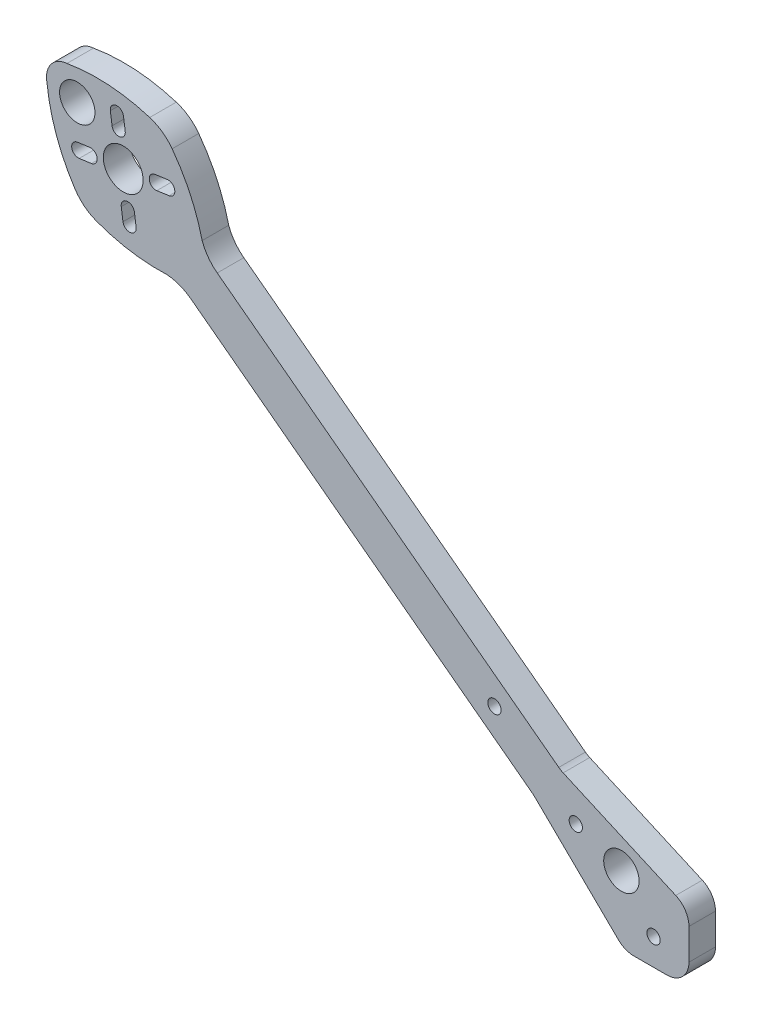
SolidWorks part; units mm, degrees
material "Thornel Mat VMA"
ref_plane "Alzado" through (0, 0, 0) normal (0, 0, 1) x (1, 0, 0)
ref_plane "Planta" through (0, 0, 0) normal (0, 1, 0) x (1, 0, 0)
ref_plane "Vista lateral" through (0, 0, 0) normal (1, 0, 0) x (0, 0, -1)
sketch "Croquis1" plane through (0, 0, 0) normal (0, 0, 1) x (1, 0, 0)
  line L0 (-166.1256, 84.824) -> (-181.6394, 96.5144) construction
  line L1 (-181.6394, 96.5144) -> (-187.6575, 88.5281) construction
  line L2 (-187.6575, 88.5281) -> (-171.8329, 76.6034) construction
  line L3 (-136.7303, 61.4124) -> (-136.7303, 68.4084)
  line L4 (-139.7056, 72.9801) -> (-165.1413, 84.2454)
  line L5 (-136.7303, 56.4124) -> (-264.512, 152.7028) construction
  line L6 (-141.7303, 56.4124) -> (-149.1592, 56.4124)
  line L7 (-152.6561, 57.8386) -> (-171.6025, 76.3779)
  line L8 (-264.512, 152.7028) -> (-274.8943, 160.5264) construction
  line L9 (-264.512, 152.7028) -> (-266.1473, 164.3384) construction
  line L11 (-267.4239, 162.6443) -> (-267.0343, 159.8715)
  line L15 (-264.0635, 160.289) -> (-264.4531, 163.0618)
  line L19 (-267.6327, 164.1297) -> (-267.4239, 162.6443) construction
  line L20 (-267.4239, 162.6443) -> (-264.4531, 163.0618) construction
  line L21 (-266.8255, 158.3861) -> (-267.0343, 159.8715) construction
  line L22 (-267.0343, 159.8715) -> (-264.0635, 160.289) construction
  line L23 (-254.5705, 155.6147) -> (-257.3433, 155.225)
  line L24 (-256.9258, 152.2542) -> (-254.153, 152.6439)
  line L25 (-261.6001, 142.7613) -> (-261.9898, 145.534)
  line L26 (-264.9606, 145.1165) -> (-264.5709, 142.3438)
  line L27 (-274.4535, 149.7908) -> (-271.6808, 150.1805)
  line L28 (-272.0983, 153.1513) -> (-274.871, 152.7616)
  line L29 (-172.0904, 76.7974) -> (-249.3006, 134.9795)
  line L30 (-264.512, 152.7028) -> (-273.5392, 140.7232) construction
  line L31 (-263.0855, 142.5525) -> (-262.8767, 141.0671) construction
  line L32 (-274.8943, 160.5264) -> (-282.8806, 166.5445) construction
  line L33 (-262.8767, 141.0671) -> (-262.3693, 137.4568) construction
  line L34 (-274.6623, 151.2762) -> (-276.1477, 151.0675) construction
  line L35 (-276.1477, 151.0675) -> (-279.6136, 150.5804) construction
  line L36 (-165.8148, 84.5898) -> (-243.2825, 142.9659)
  circle A0 centre (-180.6553, 89.5122) radius 1.5
  circle A1 centre (-162.2906, 75.6734) radius 1.5
  circle A2 centre (-151.9803, 71.6624) radius 4
  circle A3 centre (-144.7167, 62.4305) radius 1.5
  circle A5 centre (-136.7303, 56.4124) radius 10 construction
  circle A6 centre (-136.7303, 56.4124) radius 160 construction
  circle A7 centre (-264.512, 152.7028) radius 4.5
  circle A8 centre (-274.8943, 160.5264) radius 4
  arc A9 (-267.4239, 162.6443) -> (-264.4531, 163.0618) centre (-265.9385, 162.853) cw
  arc A10 (-267.0343, 159.8715) -> (-264.0635, 160.289) centre (-265.5489, 160.0803) ccw
  arc A11 (-254.5705, 155.6147) -> (-254.153, 152.6439) centre (-254.3618, 154.1293) cw
  arc A12 (-257.3433, 155.225) -> (-256.9258, 152.2542) centre (-257.1345, 153.7396) ccw
  arc A13 (-261.6001, 142.7613) -> (-264.5709, 142.3438) centre (-263.0855, 142.5525) cw
  arc A14 (-261.9898, 145.534) -> (-264.9606, 145.1165) centre (-263.4752, 145.3253) ccw
  arc A15 (-274.4535, 149.7908) -> (-274.871, 152.7616) centre (-274.6623, 151.2762) cw
  arc A16 (-271.6808, 150.1805) -> (-272.0983, 153.1513) centre (-271.8895, 151.6659) ccw
  arc A17 (-249.3006, 134.9795) -> (-254.6905, 136.9734) centre (-255.3188, 126.9931) ccw
  arc A18 (-254.6905, 136.9734) -> (-270.5641, 139.4702) centre (-256.5386, 176.9307) cw
  arc A19 (-277.233, 166.9825) -> (-281.7449, 160.995) centre (-276.8465, 161.9974) ccw
  arc A20 (-281.7449, 160.995) -> (-275.418, 143.3485) centre (-241.9768, 165.2959) ccw
  arc A21 (-270.5641, 139.4702) -> (-275.418, 143.3485) centre (-267.0577, 148.8353) cw
  arc A22 (-243.2825, 142.9659) -> (-246.6848, 147.5973) centre (-237.2643, 150.9522) cw
  arc A23 (-246.6848, 147.5973) -> (-253.4602, 162.1678) centre (-285.6036, 138.3601) ccw
  arc A24 (-253.4602, 162.1678) -> (-258.5262, 165.7647) centre (-261.4961, 156.2159) ccw
  arc A25 (-277.233, 166.9825) -> (-258.5262, 165.7647) centre (-270.4057, 127.5694) cw
  arc A26 (-149.1592, 56.4124) -> (-152.6561, 57.8386) centre (-149.1592, 61.4124) cw
  arc A27 (-136.7303, 61.4124) -> (-141.7303, 56.4124) centre (-141.7303, 61.4124) cw
  arc A28 (-136.7303, 68.4084) -> (-139.7056, 72.9801) centre (-141.7303, 68.4084) ccw
  arc A29 (-166.1256, 84.824) -> (-165.1413, 84.2454) centre (-163.1165, 88.8171) ccw
  arc A30 (-171.6025, 76.3779) -> (-172.0904, 76.7974) centre (-175.0995, 72.8042) ccw
  point P52 (-264.512, 152.7028)
  point P60 (-251.6965, 136.7849)
  point P80 (-151.1985, 56.4124)
  point P86 (-136.7303, 71.6624)
  dimension "D1" = 45
  dimension "D17" = 8
  dimension "D18" = 9
  dimension "D21" = 10
  dimension "D23" = 40
  dimension "D24" = 5
  dimension "D25" = 10
  dimension "D26" = 5
  dimension "D10" = 8
  dimension "D2" = 11.75
  dimension "D3" = 3
  dimension "D4" = 4
  dimension "D5" = 1.5
  dimension "D6" = 10
  dimension "D7" = 32.0049
  dimension "D8" = 21.5668
  dimension "D9" = 3.0015
  dimension "D12" = 22.9951
  dimension "D13" = 14.4682
  dimension "D14" = 15.25
  dimension "D15" = 100
  dimension "D16" = 13
  dimension "D19" = 10
  dimension "D20" = 15
  dimension "D22" = 5
extrude "Saliente-Extruir1" add sketch "Croquis1" along normal blind 6
